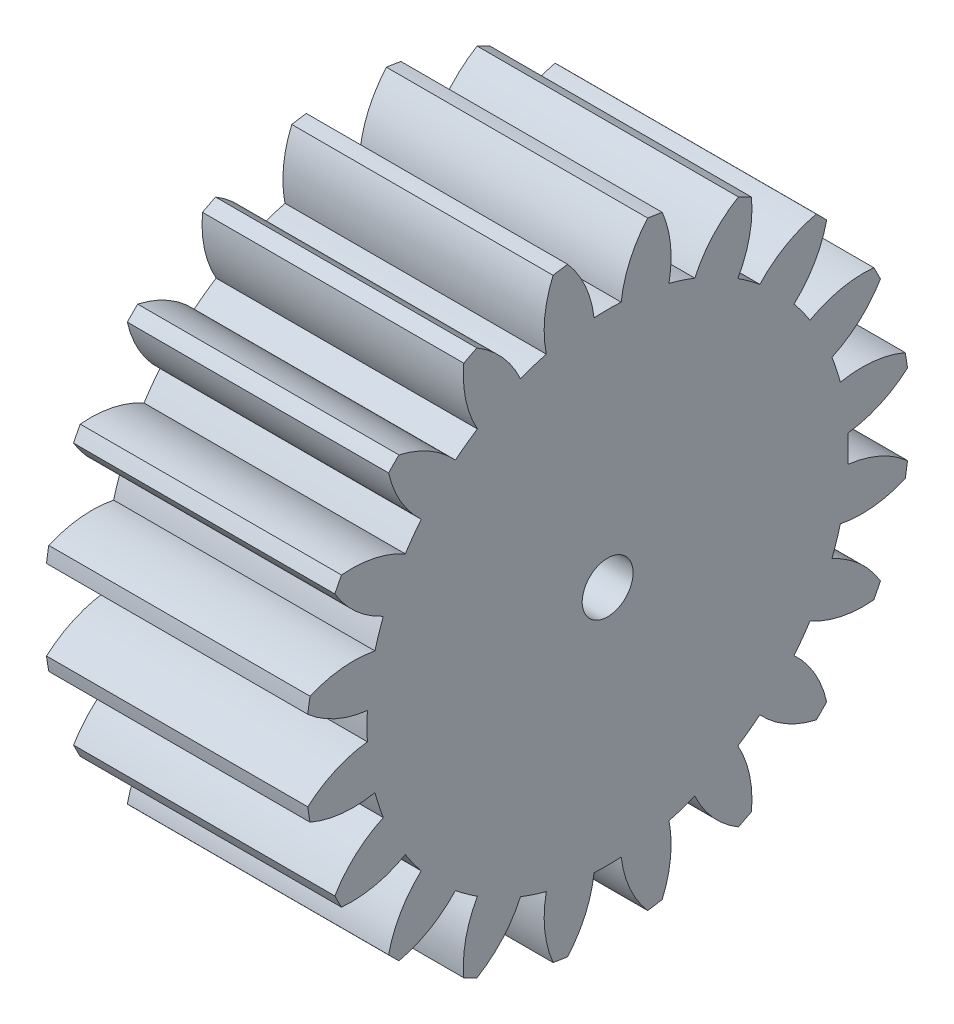
SolidWorks part; units mm, degrees
material "Delrin 2700 NC010, Low Viscosity Acetal Copolymer (SS)"
ref_plane "Plane1" through (0, 0, 0) normal (0, 0, 1) x (1, 0, 0)
ref_plane "Plane2" through (0, 0, 0) normal (0, 1, 0) x (1, 0, 0)
ref_plane "Plane3" through (0, 0, 0) normal (1, 0, 0) x (0, 0, -1)
sketch "HoldingSke" plane through (0, 0, 0) normal (0, 1, 0) x (1, 0, 0)
  line L0 (0, 0) -> (0.4698, -0.171)
  line L1 (-15, 0) -> (100, 0) construction
  line L2 (0, 0) -> (-2.1039, 2.3779)
  line L3 (0, 0) -> (-11.863, 4.5341)
  line L4 (0, 0) -> (8.1152, 2.9537)
  line L5 (0, 0) -> (-46.8476, -17.4728)
  line L6 (0, 0) -> (-4.1448, -2.7965)
  line L7 (-2.1039, 2.3779) -> (8.6586, 51.2059)
  line L8 (-76.2, 54.61) -> (-76.1, 54.61)
  line L9 (-71.009, 38.7566) -> (-53.1078, 45.2721)
  line L10 (-76.2, 71.12) -> (104.1128, 71.12)
  line L11 (0, 0) -> (-5, 0)
  line L12 (-76.2, 101.6) -> (-76.133, 101.6)
  line L13 (24.9733, 27.94) -> (52.9518, 28.4284)
  line L14 (24.9733, 27.94) -> (24.9743, 27.94)
  line L15 (24.9733, 27.94) -> (100.4006, 29.5858)
  line L16 (-63.627, -2) -> (-12.827, -2)
  circle A0 centre (0, 0) radius 0.4
  circle A1 centre (0, 0) radius 17.499
  circle A2 centre (0, 0) radius 37.5
  circle A3 centre (0, 0) radius 0.4
  dimension "MHD" = 34.998
  dimension "Hub_dia" = 75
  dimension "Bore" = 0.8
  dimension "MBD" = 0.8
  dimension "Num_teeth" = 20
  dimension "Pitch" = 0.5
  dimension "Overall_len" = 50
  dimension "Show_teeth" = 20
  dimension "Thickness" = 5
  dimension "OAL" = 50.0001
  dimension "T_dim" = 0.1
  dimension "Ap" = 20
  dimension "H" = 19.05
  dimension "Pitch_radius" = 180.3128
  dimension "Width" = 5
  dimension "Backlash" = 0.067
  dimension "Addendum_fac" = 1
  dimension "Dedendum_fac" = 1.25
  dimension "Clearance_fac" = 0.25
  dimension "Dedendum_add" = 0.001
  dimension "Module" = 2
sketch "BasProSke" plane through (0, 0, 0) normal (0, 1, 0) x (1, 0, 0)
  line L0 (-10, 0) -> (60, 0) construction
  line L1 (0, 0) -> (0, 22)
  line L2 (0, 0) -> (19, 0)
  line L3 (19, 0) -> (19, 22)
  line L4 (19, 22) -> (0, 22)
  dimension "Thickness" = 19
  dimension "Diameter" = 44
revolve "Base-Revolve" add sketch "BasProSke" angle 360 about L0
sketch "TooCutSke" plane through (0, 0, 0) normal (1, 0, 0) x (0, 0, -1)
  line L1 (0, 0) -> (0, 107) construction
  line L2 (0, 0) -> (-1.6864, 19.9288) construction
  line L3 (0, 0) -> (-6.2409, 39.4033) construction
  line L4 (-1.6864, 19.9288) -> (-3.1204, 19.7016) construction
  arc A0 (0.9862, 17.4712) -> (-0.9862, 17.4712) centre (0, 0) ccw
  arc A1 (2.9329, 21.8293) -> (-2.9329, 21.8293) centre (0, 0) ccw
  circle A2 centre (0, 0) radius 20 construction
  circle A3 centre (0, 0) radius 18.7939 construction
  arc A4 (-0.9862, 17.4712) -> (-2.9329, 21.8293) centre (-8.9313, 16.536) ccw
  arc A5 (2.9329, 21.8293) -> (0.9862, 17.4712) centre (8.9313, 16.536) ccw
  dimension "Root_dia" = 34.998
  dimension "Overcut_dia" = 44.0508
  dimension "Pitch_dia" = 40
  dimension "Base_dia" = 37.5877
  dimension "Flank_rad" = 8
  dimension "Half_ang" = 9
  dimension "Half_CT" = 1.4519
extrude "ToothCut" cut sketch "TooCutSke" along normal through all
fillet "Breaks" [suppressed] radius 0.04
fillet "RootFillets" [suppressed] radius 0.501
pattern_circular "TeethCuts" count 20 every 18 about axis through (-10, 0, 0) along (1, 0, 0) of "ToothCut", "RootFillets", "Breaks"
sketch "HubNeaOneSke" plane through (0, 0, 0) normal (-1, 0, 0) x (0, 0, 1)
  circle A0 centre (0, 0) radius 17.499
  dimension "Diameter" = 34.998
extrude "HubNearOne" [suppressed] add sketch "HubNeaOneSke" along normal blind 31.0001
sketch "HubNeaBotSke" plane through (0, 0, 0) normal (-1, 0, 0) x (0, 0, 1)
  circle A0 centre (0, 0) radius 17.499
  dimension "Diameter" = 34.998
extrude "HubNearBoth" [suppressed] add sketch "HubNeaBotSke" along normal blind 15.5
ref_plane "FarPln" through (19, 0, 0) normal (1, 0, 0) x (0, 0, -1)
sketch "HubFarSke" plane through (19, 0, 0) normal (1, 0, 0) x (0, 0, -1)
  circle A0 centre (0, 0) radius 17.499
  dimension "Diameter" = 34.998
extrude "HubFar" [suppressed] add sketch "HubFarSke" along normal blind 15.5
sketch "BorSke" plane through (0, 0, 0) normal (1, 0, 0) x (0, 0, -1)
  circle A0 centre (0, 0) radius 0.4
  dimension "Diameter" = 0.8
extrude "Bore" [suppressed] cut sketch "BorSke" along normal mid plane 100.0001
sketch "KeySke" plane through (0, 0, 0) normal (1, 0, 0) x (0, 0, -1)
  line L0 (-0.05, 0) -> (-0.05, 0.5)
  line L1 (-0.05, 0.5) -> (0.05, 0.5)
  line L2 (0.05, 0.5) -> (0.05, 0)
  line L3 (0, 0) -> (0, 34) construction
  line L4 (-0.05, 0) -> (0.05, 0)
  dimension "Offset" = 0.5
  dimension "Width" = 0.1
extrude "Keyway" [suppressed] cut sketch "KeySke" along normal mid plane 100.0001
pattern_circular "Keyway2" [suppressed] count 2 every 90 about axis through (-10, 0, 0) along (1, 0, 0)
sketch "Sketch1" plane through (19, 0, 0) normal (1, 0, 0) x (0, 0, -1)
  circle A0 centre (0, 0) radius 1.85
  dimension "D1" = 3.7
extrude "Cut-Extrude1" cut sketch "Sketch1" against normal through all
equation "' \"Module@HoldingSke\" = 6.35"
equation "' \"Num_teeth@HoldingSke\" = 12"
equation "' \"Ap@HoldingSke\" =  20"
equation "' \"Ap@HoldingSke\" = 20"
equation "' \"Width@HoldingSke\" = 0.5 * 25.4"
equation "' \"Hub_dia@HoldingSke\"= 1 * 25.4"
equation "' \"Hub_dia@HoldingSke\" = 1 * 25.4"
equation "' \"Overall_len@HoldingSke\" = 1.0 * 25.4"
equation "' \"Bore@HoldingSke\" = 0.75 * 25.4"
equation "' \"T_dim@HoldingSke\" = 0.1 * 25.4"
equation "' \"Width@KeySke\" = 0.25 * 25.4"
equation "' \"Show_teeth@HoldingSke\" = 13"
equation "' \"Backlash@HoldingSke\" = 0.009 * 25.4"
equation "' \"Addendum_fac@HoldingSke\" = 1.0"
equation "' \"Dedendum_fac@HoldingSke\" = 1.25"
equation "' \"Dedendum_add@HoldingSke\" = 0.00005 * 25.4"
equation "' \"Clearance_fac@HoldingSke\" = 0.25"
equation "\"Pitch@HoldingSke\" = 1 / \"Module@HoldingSke\""
equation "\"Overcut_dia@TooCutSke\" = (\"Num_teeth@HoldingSke\" + 2 * \"Addendum_fac@HoldingSke\") / \"Pitch@HoldingSke\" + 0.002 * 25.4"
equation "\"Pitch_dia@TooCutSke\" = \"Num_teeth@HoldingSke\" / \"Pitch@HoldingSke\""
equation "\"Base_dia@TooCutSke\" = \"Num_teeth@HoldingSke\" / \"Pitch@HoldingSke\" * cos((\"Ap@HoldingSke\"  * 3.14159265 / 180))"
equation "\"Root_dia@TooCutSke\" = (\"Num_teeth@HoldingSke\" + 2) / \"Pitch@HoldingSke\" - 2 * (\"Addendum_fac@HoldingSke\" + \"Dedendum_fac@HoldingSke\") / \"Pitch@HoldingSke\" - \"Dedendum_add@HoldingSke\" * 2"
equation "\"Half_ang@TooCutSke\" = 180 / \"Num_teeth@HoldingSke\""
equation "\"Half_CT@TooCutSke\" = \"Num_teeth@HoldingSke\" / \"Pitch@HoldingSke\" * sin((3.14159265 / 2 / \"Num_teeth@HoldingSke\")) / 2 - 7 * \"Backlash@HoldingSke\" / 4"
equation "\"Flank_rad@TooCutSke\" = \"Num_teeth@HoldingSke\" / \"Pitch@HoldingSke\" / 5"
equation "\"Radius@RootFillets\" = \"Clearance_fac@HoldingSke\" / \"Pitch@HoldingSke\" + \"Dedendum_add@HoldingSke\""
equation "\"Break_rad@Breaks\" = 0.02 / \"Pitch@HoldingSke\""
equation "\"Thickness@HoldingSke\" = \"Width@HoldingSke\""
equation "\"OAL@HoldingSke\" = \"Thickness@HoldingSke\""
equation "\"MHD@HoldingSke\" = (\"Num_teeth@HoldingSke\" + 2) / \"Pitch@HoldingSke\" - 2 * (\"Addendum_fac@HoldingSke\" + \"Dedendum_fac@HoldingSke\")  / \"Pitch@HoldingSke\" - \"Dedendum_add@HoldingSke\" * 2"
equation "\"MBD@HoldingSke\" = (\"Num_teeth@HoldingSke\" + 2) / \"Pitch@HoldingSke\" - 2 * (\"Addendum_fac@HoldingSke\" + \"Dedendum_fac@HoldingSke\")  / \"Pitch@HoldingSke\" - \"Dedendum_add@HoldingSke\" * 2 - 0.002 * 25.4"
equation "\"MHD@HoldingSke\" = ((sgn( \"MHD@HoldingSke\" - \"Hub_dia@HoldingSke\" )-1)*( \"MHD@HoldingSke\" - \"Hub_dia@HoldingSke\" ))/-2+ \"Hub_dia@HoldingSke\""
equation "\"MBD@HoldingSke\" = ((sgn( \"MBD@HoldingSke\" - \"Bore@HoldingSke\" )-1)*( \"MBD@HoldingSke\" - \"Bore@HoldingSke\" ))/-2+ \"Bore@HoldingSke\""
equation "\"OAL@HoldingSke\" = ((sgn( \"OAL@HoldingSke\" - \"Overall_len@HoldingSke\" )+1)*( \"OAL@HoldingSke\" - \"Overall_len@HoldingSke\" ))/2 + \"Overall_len@HoldingSke\" + 0.000002 * 25.4"
equation "\"Num_teeth@TeethCuts\" = int( \"Show_teeth@HoldingSke\" ) + 1"
equation "\"Num_teeth@TeethCuts\" = ((sgn( \"Num_teeth@TeethCuts\" - \"Num_teeth@HoldingSke\" )-1)*( \"Num_teeth@TeethCuts\" - \"Num_teeth@HoldingSke\" ))/-2+ \"Num_teeth@HoldingSke\""
equation "\"Num_teeth@TeethCuts\" = ((sgn( \"Num_teeth@TeethCuts\" - 2.0)+1)*( \"Num_teeth@TeethCuts\" - 2.0))/2 +2.0"
equation "\"Angle@TeethCuts\" = 360.0 / \"Num_teeth@HoldingSke\""
equation "\"Diameter@BasProSke\" = (\"Num_teeth@HoldingSke\" + 2 * \"Addendum_fac@HoldingSke\") / \"Pitch@HoldingSke\""
equation "' \"Fillet_rad@BasProSke\" =  \"Thickness@HoldingSke\" * 0.05"
equation "' \"Fillet_rad@BasProSke\" = \"Thickness@HoldingSke\" * 0.05"
equation "\"MHD@HoldingSke\" = ((sgn( \"MHD@HoldingSke\" - \"Root_dia@TooCutSke\" )-1)*( \"MHD@HoldingSke\" - \"Root_dia@TooCutSke\" ))/-2+ \"Root_dia@TooCutSke\""
equation "\"Diameter@HubNeaOneSke\" = \"MHD@HoldingSke\""
equation "\"Length@HubNearOne\" = \"OAL@HoldingSke\" - \"Thickness@BasProSke\""
equation "\"Diameter@HubNeaBotSke\" = \"MHD@HoldingSke\""
equation "\"Length@HubNearBoth\" = ( \"OAL@HoldingSke\" - \"Thickness@BasProSke\" ) / 2.0"
equation "\"Thickness@FarPln\" = \"Thickness@BasProSke\""
equation "\"Diameter@HubFarSke\" = \"MHD@HoldingSke\""
equation "\"Length@HubFar\" = ( \"OAL@HoldingSke\" - \"Thickness@BasProSke\" ) / 2.0"
equation "\"Diameter@BorSke\" = \"MBD@HoldingSke\""
equation "\"D1@Bore\" = \"OAL@HoldingSke\" * 2.0"
equation "\"D1@Keyway\" = \"OAL@HoldingSke\" * 2.0"
equation "\"Offset@KeySke\" = \"T_dim@HoldingSke\" + \"MBD@HoldingSke\" / 2.0"
